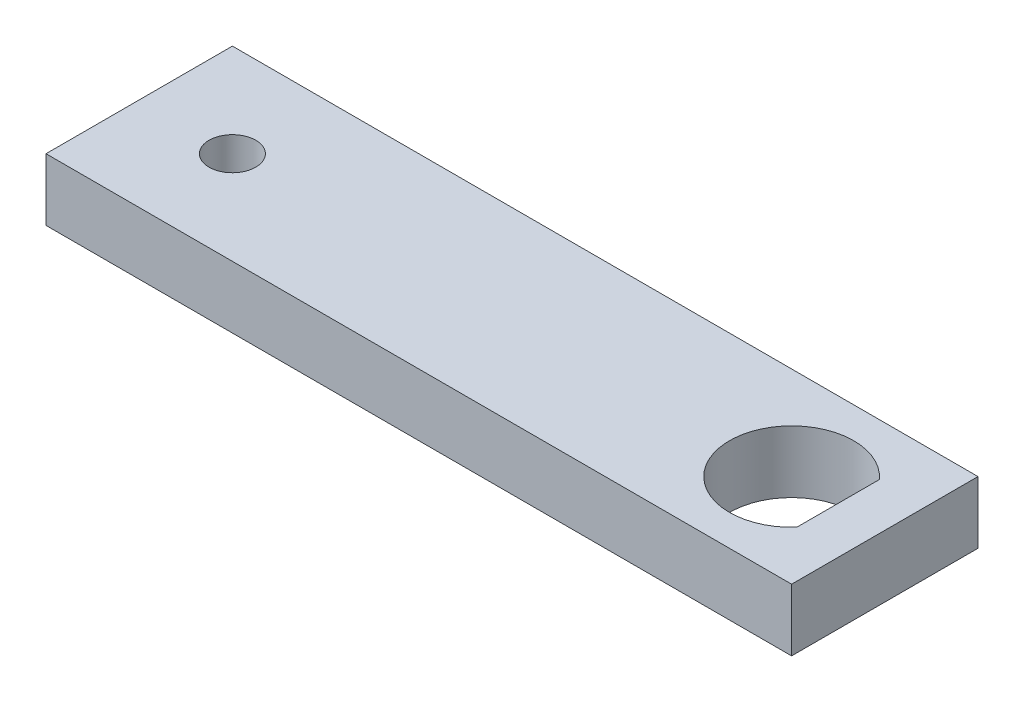
SolidWorks part; units mm, degrees
ref_plane "정면" through (0, 0, 0) normal (0, 0, 1) x (1, 0, 0)
ref_plane "윗면" through (0, 0, 0) normal (0, 1, 0) x (1, 0, 0)
ref_plane "우측면" through (0, 0, 0) normal (1, 0, 0) x (0, 0, -1)
ref_plane "평면1" through (0, 6.35, 0) normal (0, 1, 0) x (1, 0, 0)
sketch "스케치1" plane through (0, 6.35, 0) normal (0, 1, 0) x (1, 0, 0)
  line L0 (4.7498, 4.2145) -> (4.7498, -4.2145)
  line L1 (-66.675, 9.525) -> (-66.675, -9.525)
  line L2 (-66.675, -9.525) -> (9.525, -9.525)
  line L3 (9.525, -9.525) -> (9.525, 9.525)
  line L4 (9.525, 9.525) -> (-66.675, 9.525)
  arc A0 (4.7498, -4.2145) -> (4.7498, 4.2145) centre (0, 0) cw
  circle A1 centre (-57.15, 0) radius 2.3876
extrude "보스-돌출1" add sketch "스케치1" against normal blind 6.35
